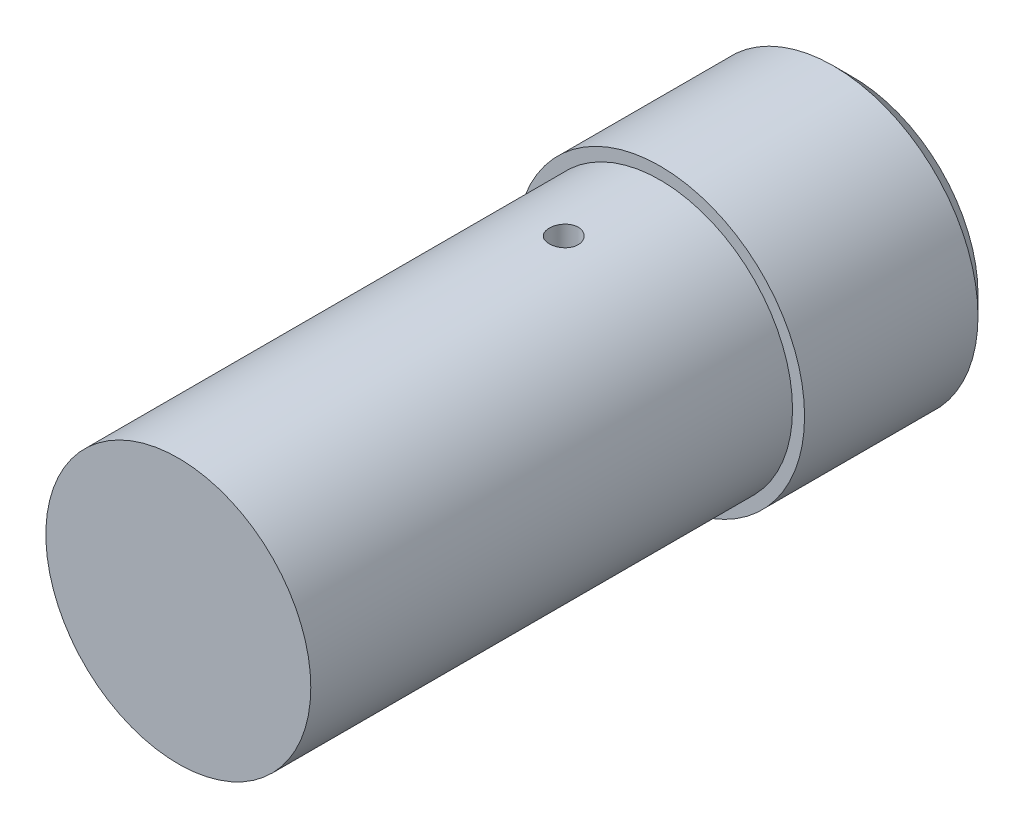
SolidWorks part; units mm, degrees
material "PW100:Mi:0:32:C1:0:1:2:Re:8:"
ref_plane "Plan1" through (0, 0, 0) normal (0, 0, 1) x (1, 0, 0)
ref_plane "Plan2" through (0, 0, 0) normal (0, 1, 0) x (1, 0, 0)
ref_plane "Plan3" through (0, 0, 0) normal (1, 0, 0) x (0, 0, -1)
sketch "Esquisse1" plane through (0, 0, 0) normal (0, 0, 1) x (1, 0, 0)
  circle A0 centre (0, 0) radius 30
extrude "Base-Extrusion" add sketch "Esquisse1" along normal blind 40
sketch "Esquisse2" plane through (0, 0, 40) normal (0, 0, 1) x (1, 0, 0)
  circle A0 centre (0, 0) radius 27.5
  dimension "D1" = 55
extrude "Boss.-Extru.1" add sketch "Esquisse2" along normal blind 100
ref_plane "Plan4" through (0, 30, 0) normal (0, 1, 0) x (-1, 0, 0)
sketch "Esquisse3" plane through (0, 30, 0) normal (0, 1, 0) x (-1, 0, 0)
  line L0 (0, 40) -> (0, 0) construction
  circle A0 centre (0, 60) radius 3
extrude "Enlèv. mat.-Extru.1" cut sketch "Esquisse3" against normal blind 30
chamfer "Chanfrein1" distance 4 angle 45 1 edges at (30, 0, 0)
ref_plane "Plan5" through (0, 0, 34) normal (0, 0, 1) x (1, 0, 0)
sketch "G2" plane through (0, 0, 34) normal (0, 0, 1) x (1, 0, 0)
  point P0 (0, 0)
